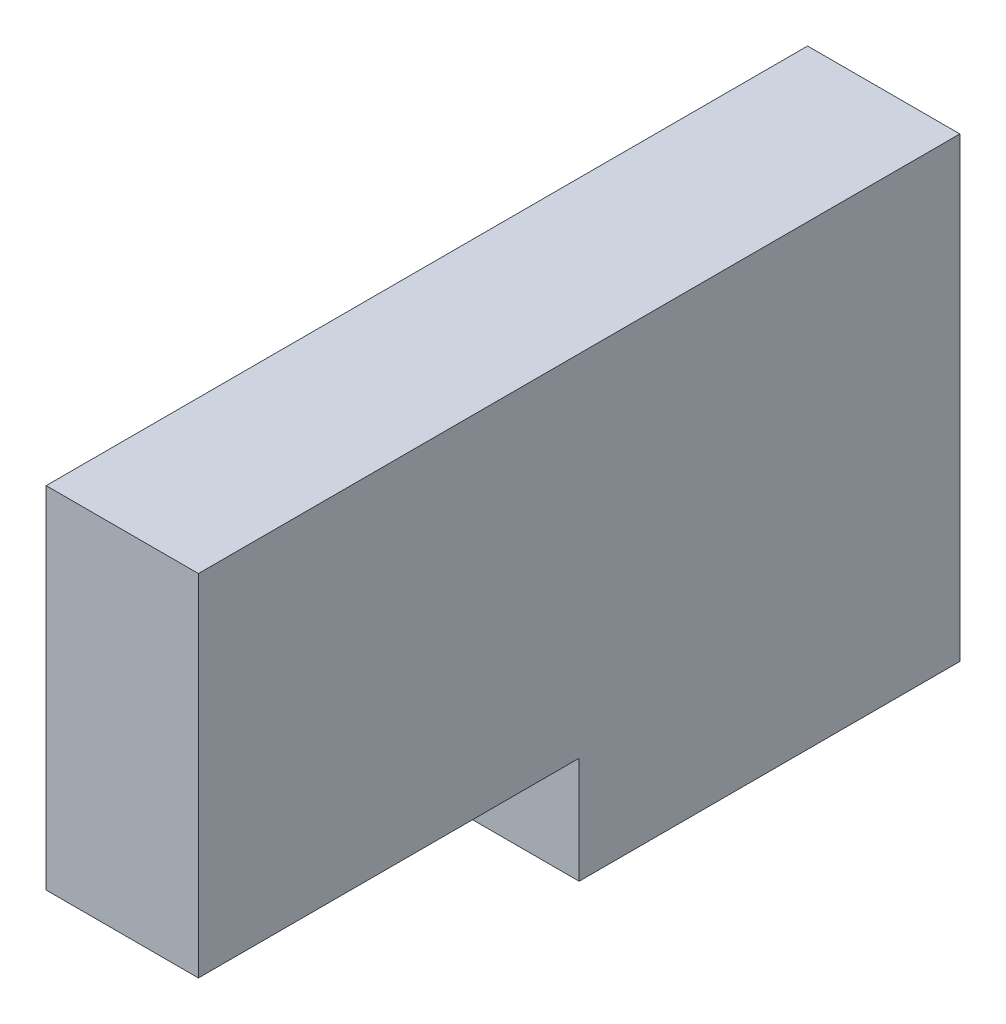
SolidWorks part; units mm, degrees
ref_plane "Plan de face" through (0, 0, 0) normal (0, 0, 1) x (1, 0, 0)
ref_plane "Plan de dessus" through (0, 0, 0) normal (0, 1, 0) x (1, 0, 0)
ref_plane "Plan de droite" through (0, 0, 0) normal (1, 0, 0) x (0, 0, -1)
sketch "Esquisse1" plane through (0, 0, 0) normal (0, 0, 1) x (1, 0, 0)
  line L0 (5, 30) -> (5, 0) construction
  line L1 (0, 0) -> (10, 0)
  line L2 (0, 0) -> (0, 30)
  line L3 (0, 30) -> (10, 30)
  line L4 (10, 0) -> (10, 30)
  circle A0 centre (5, 5) radius 1.75
  circle A1 centre (5, 15) radius 1.75
  circle A2 centre (5, 25) radius 1.75
  dimension "D3" = 3.5
  dimension "D4" = 5
  dimension "D1" = 10
  dimension "D2" = 30
  dimension "D5" = 10
  dimension "D6" = 10
extrude "Boss.-Extru.1" add sketch "Esquisse1" along normal blind 20
sketch "Esquisse2" plane through (0, 0, 20) normal (0, 0, 1) x (1, 0, 0)
  line L1 (0, 0) -> (10, 0)
  line L2 (0, 0) -> (0, 30)
  line L3 (0, 30) -> (10, 30)
  line L4 (10, 0) -> (10, 30)
extrude "Boss.-Extru.2" add sketch "Esquisse2" along normal blind 5
sketch "Esquisse3" plane through (0, 0, 25) normal (0, 0, 1) x (1, 0, 0)
  line L0 (10, 0) -> (10, 30) construction
  line L1 (0, 30) -> (10, 30)
  line L2 (0, 30) -> (0, 7)
  line L3 (0, 7) -> (10, 7)
  line L4 (10, 30) -> (10, 7)
  line L5 (0, 0) -> (10, 0) construction
  dimension "D1" = 7
extrude "Boss.-Extru.3" add sketch "Esquisse3" along normal blind 25
sketch "Esquisse4" plane through (0, 7, 0) normal (0, -1, 0) x (-1, 0, 0)
  line L0 (-5, -50) -> (-5, -25) construction
  line L1 (0, -50) -> (-10, -50) construction
  line L2 (0, -25) -> (-10, -25) construction
  circle A0 centre (-5, -45) radius 1.75
  circle A1 centre (-5, -35) radius 1.75
  dimension "D1" = 3.5
  dimension "D2" = 10
  dimension "D4" = 5
extrude "Enlèv. mat.-Extru.1" cut sketch "Esquisse4" against normal blind 15
